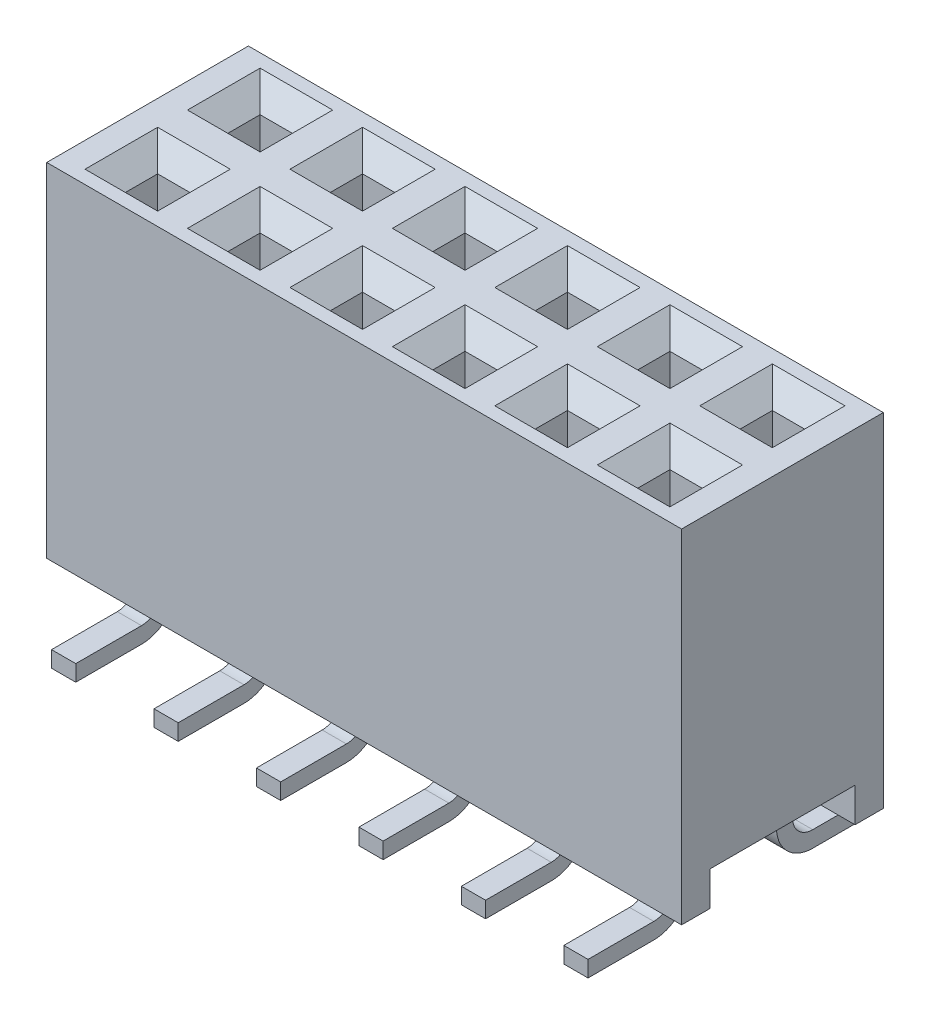
SolidWorks part; units mm, degrees
ref_plane "Спереди" through (0, 0, 0) normal (0, 0, 1) x (1, 0, 0)
ref_plane "Сверху" through (0, 0, 0) normal (0, 1, 0) x (1, 0, 0)
ref_plane "Справа" through (0, 0, 0) normal (1, 0, 0) x (0, 0, -1)
sketch "Эскиз1" plane through (0, 0, 0) normal (1, 0, 0) x (0, 0, -1)
  line L0 (-2.5, 1.2) -> (-2.5, 9.7)
  line L1 (-2.5, 9.7) -> (2.5, 9.7)
  line L2 (2.5, 9.7) -> (2.5, 1.2)
  line L3 (2.5, 1.2) -> (1.8, 1.2)
  line L4 (1.8, 1.2) -> (1.8, 2.05)
  line L5 (1.8, 2.05) -> (-1.8, 2.05)
  line L6 (-1.8, 2.05) -> (-1.8, 1.2)
  line L7 (-1.8, 1.2) -> (-2.5, 1.2)
  point P2 (0, 2.05)
  dimension "D1" = 5
  dimension "D2" = 8.5
  dimension "D3" = 0.85
  dimension "D4" = 0.7
  dimension "D5" = 1.2
extrude "Бобышка-Вытянуть1" add sketch "Эскиз1" against normal mid plane 15.74
sketch "Эскиз2" plane through (0, 9.7, 0) normal (0, 1, 0) x (1, 0, 0)
  line L1 (6.75, -1.67) -> (5.95, -1.67)
  line L2 (6.75, -1.67) -> (6.75, -0.87)
  line L3 (6.75, -0.87) -> (5.95, -0.87)
  line L4 (5.95, -1.67) -> (5.95, -0.87)
  line L5 (7.87, 2.5) -> (7.87, -2.5) construction
  point P4 (5.95, -1.27)
  point P8 (6.35, -1.67)
  dimension "D1" = 0.8
  dimension "D2" = 0.8
  dimension "D3" = 1.27
  dimension "D4" = 1.52
extrude "Вырез-Вытянуть1" cut sketch "Эскиз2" against normal through all
chamfer "Фаска1" distance 0.5 angle 45 4 edges at (6.75, 9.7, 1.27) (6.35, 9.7, 0.87) (5.95, 9.7, 1.27) (6.35, 9.7, 1.67)
pattern_linear "Линейный массив1" count 6 spacing 2.54 along (-1, 0, 0) count 2 spacing 2.54 along (0, 0, -1) of "Фаска1", "Вырез-Вытянуть1"
ref_plane "Плоскость1" through (6.35, 0, 0) normal (1, 0, 0) x (0, 0, -1)
sketch "Эскиз3" plane through (6.35, 0, 0) normal (1, 0, 0) x (0, 0, -1)
  line L0 (-1.07, 0.9) -> (-1.07, 2.05)
  line L1 (-1.07, 2.05) -> (-1.47, 2.05)
  line L2 (-1.47, 2.05) -> (-1.47, 0.9)
  line L3 (-1.97, 0.4) -> (-3.6, 0.4)
  line L4 (-3.6, 0.4) -> (-3.6, 0)
  line L5 (-3.6, 0) -> (-1.97, 0)
  line L6 (-1.8, 2.05) -> (1.8, 2.05) construction
  arc A0 (-1.47, 0.9) -> (-1.97, 0.4) centre (-1.97, 0.9) cw
  arc A1 (-1.07, 0.9) -> (-1.97, 0) centre (-1.97, 0.9) cw
  point P8 (-1.27, 2.05)
  dimension "D4" = 0.5
  dimension "D1" = 0.4
  dimension "D2" = 1.27
  dimension "D3" = 3.6
extrude "Бобышка-Вытянуть2" add sketch "Эскиз3" along normal mid plane 0.6 separate body
mirror "Зеркальное отражение1" about plane through (0, 0, 0) normal (0, 0, 1) of bodies 104 112 111 110 109 105 106 107 108 122 124 125 141 144 139 142 140 143 127 130 133 128 131 126 129 132 138 137 136 134 135 145 146 147 148 149 150 151 152 153
pattern_linear "Линейный массив2" count 6 spacing 2.54 along (-1, 0, 0) of bodies 117 104
equation "\"Num\" = 6"
equation "\"BodyLenght\"= \"Num\" * 2.54 + 0.5мм"
equation "\"D1@Бобышка-Вытянуть1\" = \"BodyLenght\""
equation "\"D1@Линейный массив1\" = \"Num\""
equation "\"D1@Линейный массив2\" = \"Num\""
